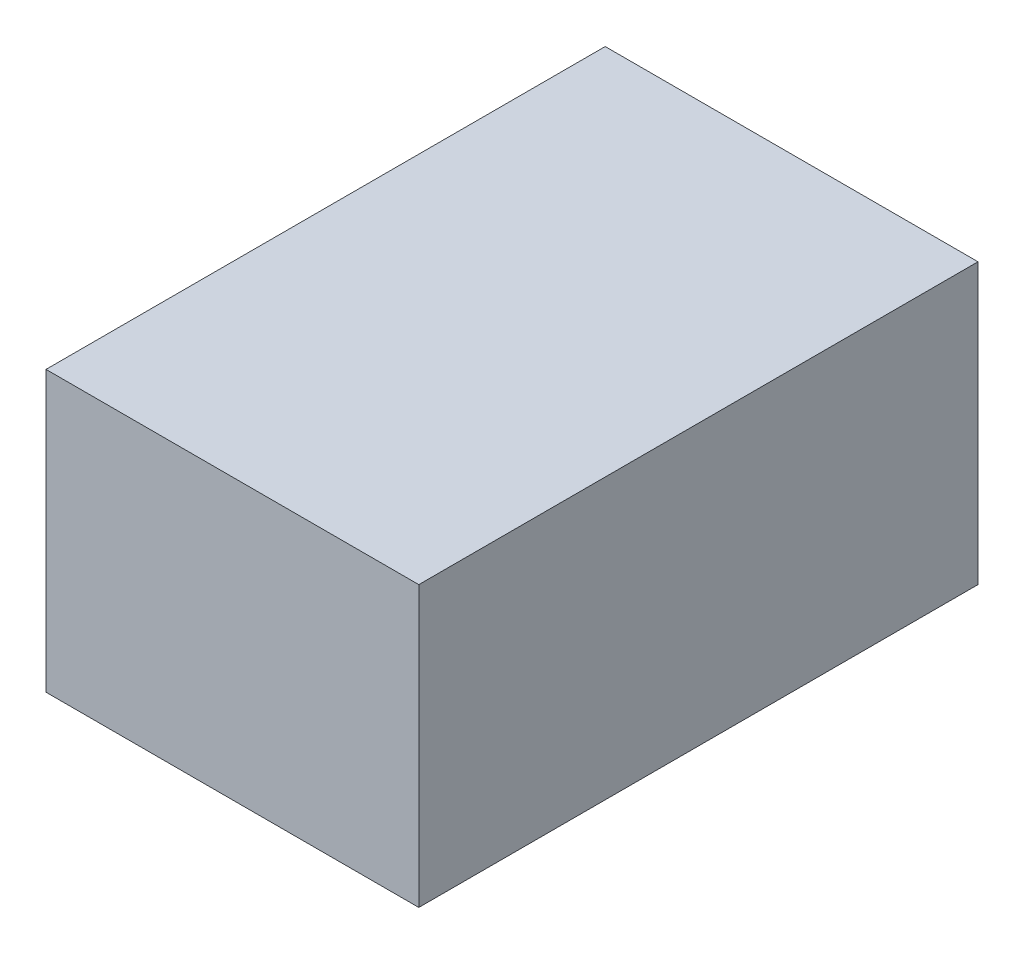
SolidWorks part; units mm, degrees
ref_plane "Front Plane" through (0, 0, 0) normal (0, 0, 1) x (1, 0, 0)
ref_plane "Top Plane" through (0, 0, 0) normal (0, 1, 0) x (1, 0, 0)
ref_plane "Right Plane" through (0, 0, 0) normal (1, 0, 0) x (0, 0, -1)
sketch "Sketch1" plane through (0, 0, 0) normal (0, 1, 0) x (1, 0, 0)
  line L1 (0, 0) -> (609.6, 0)
  line L2 (0, 0) -> (0, 914.4)
  line L3 (0, 914.4) -> (609.6, 914.4)
  line L4 (609.6, 0) -> (609.6, 914.4)
  dimension "D1" = 914.4
  dimension "D2" = 609.6
extrude "Boss-Extrude1" add sketch "Sketch1" along normal blind 457.2
